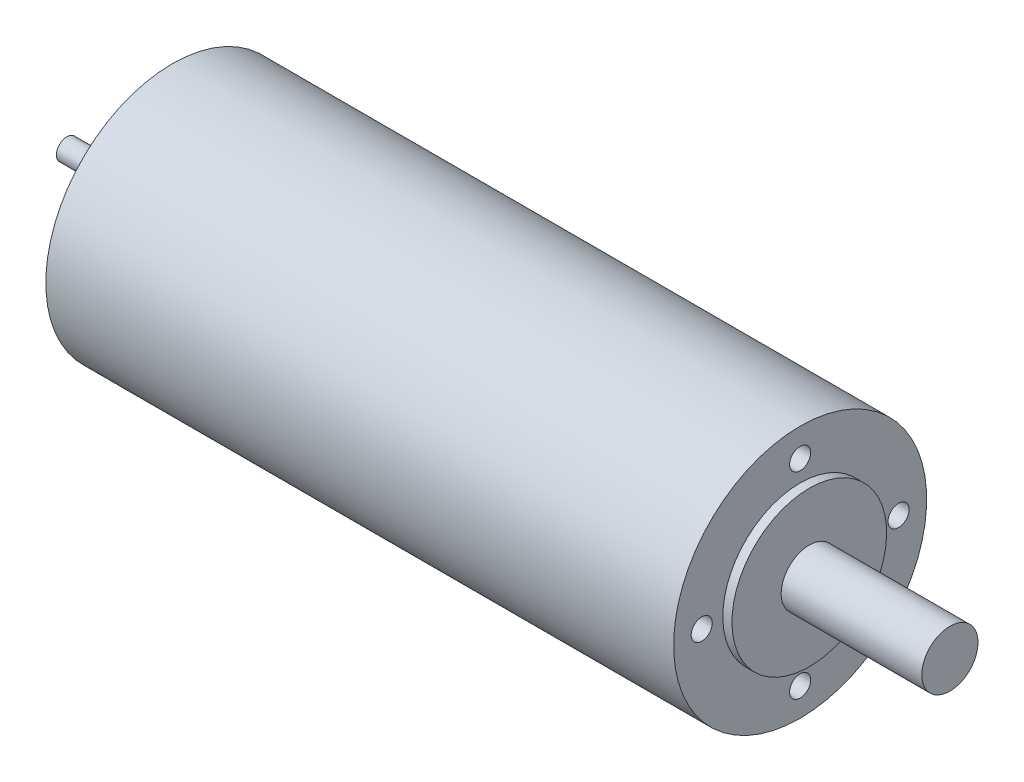
SolidWorks part; units mm, degrees
ref_plane "Front Plane" through (0, 0, 0) normal (0, 0, 1) x (1, 0, 0)
ref_plane "Top Plane" through (0, 0, 0) normal (0, 1, 0) x (1, 0, 0)
ref_plane "Right Plane" through (0, 0, 0) normal (1, 0, 0) x (0, 0, -1)
sketch "Sketch1" plane through (0, 0, 0) normal (0, 0, 1) x (1, 0, 0)
  line L0 (0, 0) -> (0, 18)
  line L1 (0, 18) -> (89.3, 18)
  line L2 (89.3, 18) -> (89.3, 11)
  line L3 (89.3, 11) -> (90.6, 11)
  line L4 (90.6, 11) -> (90.6, 4)
  line L5 (90.6, 4) -> (110.6, 4)
  line L6 (110.6, 4) -> (110.6, 0)
  line L7 (110.6, 0) -> (0, 0)
  line L8 (0, 12) -> (-4, 12)
  line L9 (-4, 12) -> (-4, 1.5)
  line L10 (-4, 1.5) -> (-15, 1.5)
  line L11 (-15, 1.5) -> (-15, 0)
  line L12 (-15, 0) -> (0, 0)
  dimension "D1" = 4
  dimension "D2" = 11
  dimension "D3" = 18
  dimension "D4" = 1.3
  dimension "D5" = 21.3
  dimension "D6" = 89.3
  dimension "D7" = 1.5
  dimension "D8" = 11
  dimension "D9" = 12
  dimension "D10" = 4
revolve "Revolve1" add sketch "Sketch1" angle 360 about L7
sketch "Sketch2" plane through (89.3, 0, 0) normal (1, 0, 0) x (0, 0, -1)
  circle A0 centre (0, 14) radius 1.5
  circle A1 centre (14, 0) radius 1.5
  circle A2 centre (0, -14) radius 1.5
  circle A3 centre (-14, 0) radius 1.5
  point P2 (0, 0)
  point P4 (14.2138, -4.2232)
  point P5 (0, 0)
  point P12 (0, 0)
  dimension "D2" = 3
  dimension "D1" = 14
  dimension "D3" = 4
extrude "Cut-Extrude1" cut sketch "Sketch2" against normal blind 10
